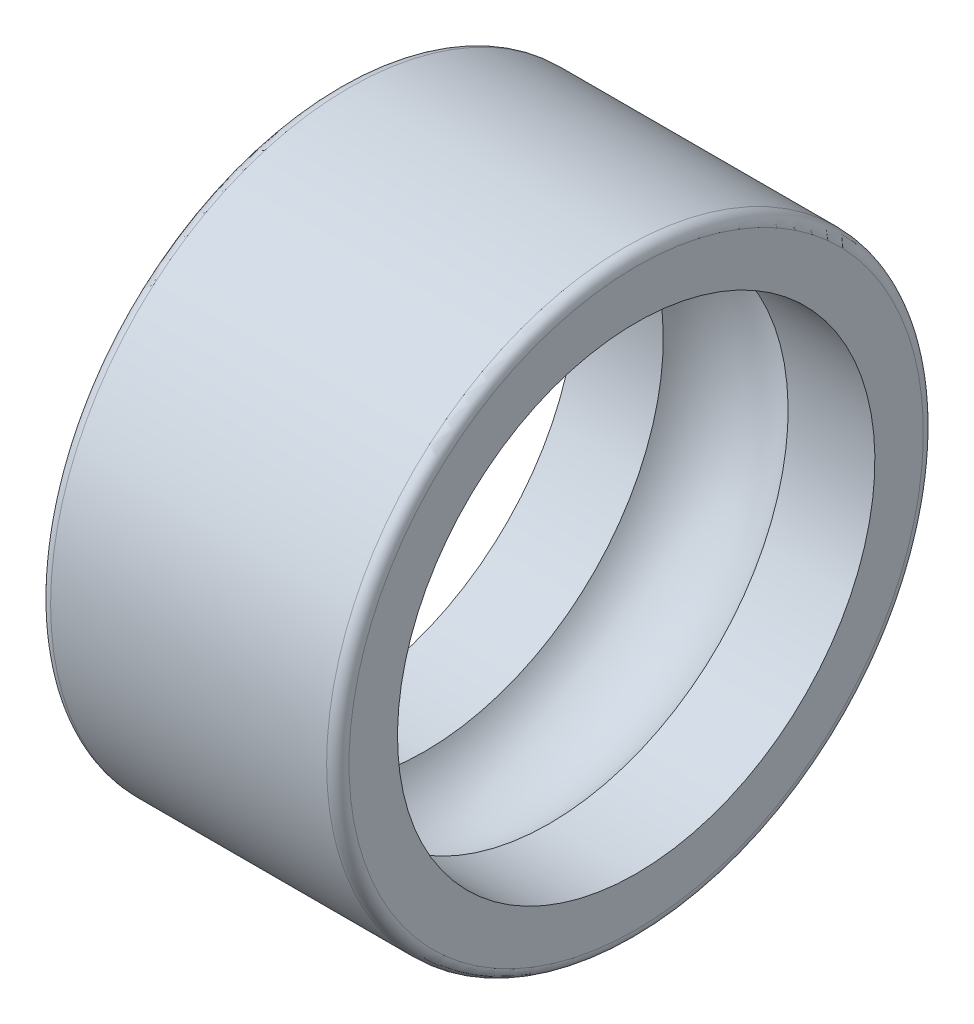
SolidWorks part; units mm, degrees
ref_plane "Plan de face" through (0, 0, 0) normal (0, 0, 1) x (1, 0, 0)
ref_plane "Plan de dessus" through (0, 0, 0) normal (0, 1, 0) x (1, 0, 0)
ref_plane "Plan de droite" through (0, 0, 0) normal (1, 0, 0) x (0, 0, -1)
sketch "Esquisse1" plane through (0, 0, 0) normal (0, 0, 1) x (1, 0, 0)
  line L0 (2, 4) -> (2, 1.5) construction
  line L1 (0.15, 4) -> (3.85, 4)
  line L2 (0, 3.85) -> (0, 1.65) construction
  line L3 (0.15, 1.5) -> (3.85, 1.5) construction
  line L4 (4, 3.85) -> (4, 1.65) construction
  line L5 (4, 3.2) -> (2.8367, 3.2)
  line L6 (4, 2.3) -> (0, 2.3) construction
  line L7 (0, 0) -> (4, 0) construction
  line L8 (4, 3.85) -> (4, 3.2)
  line L9 (0, 3.2) -> (0, 3.85)
  line L10 (1.1633, 3.2) -> (0, 3.2)
  arc A1 (0, 1.65) -> (0.15, 1.5) centre (0.15, 1.65) ccw construction
  arc A2 (0.15, 4) -> (0, 3.85) centre (0.15, 3.85) ccw
  arc A3 (4, 3.85) -> (3.85, 4) centre (3.85, 3.85) ccw
  arc A4 (3.85, 1.5) -> (4, 1.65) centre (3.85, 1.65) ccw construction
  arc A5 (2.8367, 3.2) -> (1.1633, 3.2) centre (2, 2.75) ccw
  dimension "D4" = 0.15
  dimension "D5" = 1.9
  dimension "D1" = 1.5
  dimension "D2" = 4
  dimension "D3" = 4
  dimension "D6" = 2.3
  dimension "D7" = 3.2
revolve "Révolution1" add sketch "Esquisse1" angle 360 about L7
